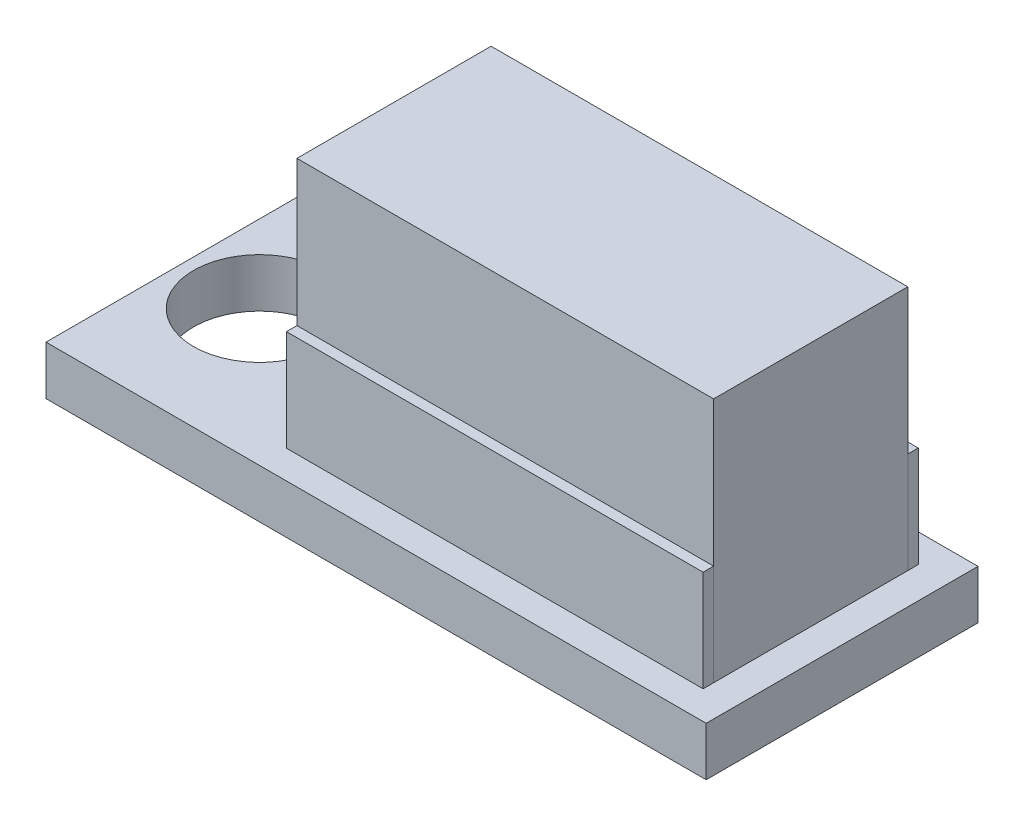
SolidWorks part; units mm, degrees
ref_plane "Front Plane" through (0, 0, 0) normal (0, 0, 1) x (1, 0, 0)
ref_plane "Top Plane" through (0, 0, 0) normal (0, 1, 0) x (1, 0, 0)
ref_plane "Right Plane" through (0, 0, 0) normal (1, 0, 0) x (0, 0, -1)
sketch "Sketch1" plane through (0, 0, 0) normal (0, 1, 0) x (1, 0, 0)
  line L0 (-51.695, -20.5365) -> (-30.105, -20.5365) construction
  line L1 (-51.695, -16.0915) -> (-30.105, -16.0915)
  line L2 (-51.695, -16.0915) -> (-51.695, -24.9815)
  line L3 (-51.695, -24.9815) -> (-30.105, -24.9815)
  line L4 (-30.105, -16.0915) -> (-30.105, -24.9815)
  circle A0 centre (-49.155, -20.5365) radius 2.159
  dimension "D3" = 19.05
  dimension "D1" = 21.59
  dimension "D2" = 8.89
extrude "Boss-Extrude1" add sketch "Sketch1" along normal blind 1.6002
sketch "Sketch2" plane through (0, 0, 0) normal (0, 1, 0) x (1, 0, 0)
  line L1 (-31.1315, -17.0186) -> (-44.7586, -17.0186)
  line L2 (-31.1315, -17.0186) -> (-31.1315, -24.0544)
  line L3 (-31.1315, -24.0544) -> (-44.7586, -24.0544)
  line L4 (-44.7586, -17.0186) -> (-44.7586, -24.0544)
  line L6 (-30.105, -24.9815) -> (-30.105, -16.0915) construction
  line L7 (-49.155, -20.5365) -> (-27.163, -20.5365) construction
  dimension "D1" = 7.0358
  dimension "D3" = 13.6271
  dimension "D4" = 1.0265
extrude "Boss-Extrude2" add sketch "Sketch2" along normal blind 4.9022
sketch "Sketch3" plane through (0, 0, 0) normal (0, 1, 0) x (1, 0, 0)
  line L0 (-44.7586, -17.0186) -> (-44.7586, -24.0544) construction
  line L1 (-44.7586, -17.3615) -> (-31.1315, -17.3615)
  line L2 (-44.7586, -17.3615) -> (-44.7586, -23.7115)
  line L3 (-44.7586, -23.7115) -> (-31.1315, -23.7115)
  line L4 (-31.1315, -17.3615) -> (-31.1315, -23.7115)
  line L5 (-31.1315, -24.0544) -> (-31.1315, -17.0186) construction
  line L8 (-49.155, -20.5365) -> (-26.3322, -20.5365) construction
  dimension "D1" = 6.35
extrude "Boss-Extrude3" add sketch "Sketch3" along normal blind 9.6393 separate body
